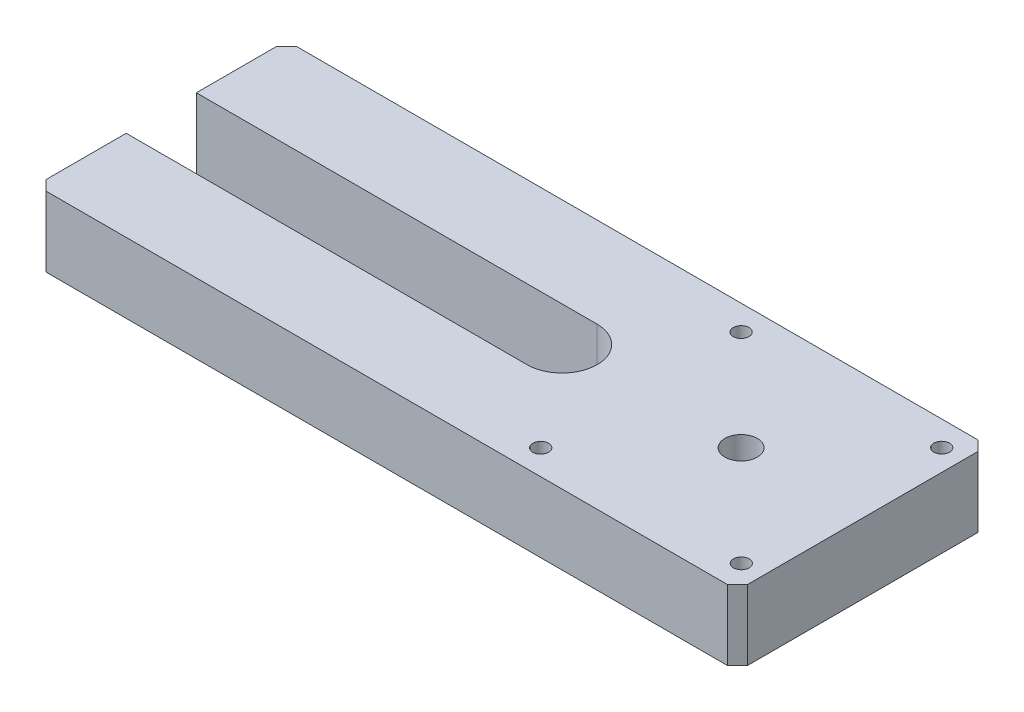
SolidWorks part; units mm, degrees
ref_plane "Front Plane" through (0, 0, 0) normal (0, 0, 1) x (1, 0, 0)
ref_plane "Top Plane" through (0, 0, 0) normal (0, 1, 0) x (1, 0, 0)
ref_plane "Right Plane" through (0, 0, 0) normal (1, 0, 0) x (0, 0, -1)
sketch "Sketch1" plane through (0, 0, 0) normal (0, 1, 0) x (1, 0, 0)
  line L0 (0, 0) -> (68.006, 0)
  line L1 (68.006, 0) -> (69.003, 0.997)
  line L2 (69.003, 0.997) -> (69.003, 24.003)
  line L3 (69.003, 24.003) -> (68.006, 25)
  line L4 (68.006, 25) -> (0, 25)
  line L5 (0, 25) -> (-0.997, 24.003)
  line L6 (-0.997, 24.003) -> (-0.997, 0.997)
  line L7 (-0.997, 0.997) -> (0, 0)
  line L8 (-0.997, 12.5) -> (69.003, 12.5) construction
  line L9 (56.866, 22.5208) -> (56.866, -1.4885) construction
  circle A4 centre (66.866, 2.5208) radius 0.785
  circle A5 centre (66.866, 22.5208) radius 0.785
  circle A6 centre (46.866, 22.5) radius 0.785
  circle A7 centre (46.866, 2.5) radius 0.785
  circle A8 centre (56.866, 12.5) radius 1.62
  point P19 (0, 0)
  point P20 (0, 0)
  point P27 (46.9572, 3.2797)
  dimension "D2" = 25
  dimension "D4" = 1.14
  dimension "D5" = 10
  dimension "D1" = 1.14
  dimension "D3" = 70
extrude "Boss-Extrude1" add sketch "Sketch1" along normal blind 7
sketch "Sketch2" plane through (0, 7, 0) normal (0, 1, 0) x (1, 0, 0)
  line L0 (-0.997, 12.5) -> (39.003, 12.5) construction
  line L1 (-0.997, 24.003) -> (-0.997, 0.997) construction
  line L2 (-0.997, 16) -> (39.003, 16)
  line L3 (-0.997, 9) -> (39.003, 9)
  arc A0 (-0.997, 16) -> (-0.997, 9) centre (-0.997, 12.5) ccw
  arc A1 (39.003, 9) -> (39.003, 16) centre (39.003, 12.5) ccw
  point P4 (19.003, 12.5)
  dimension "D1" = 7
  dimension "D2" = 40
extrude "Cut-Extrude1" cut sketch "Sketch2" against normal blind 7
